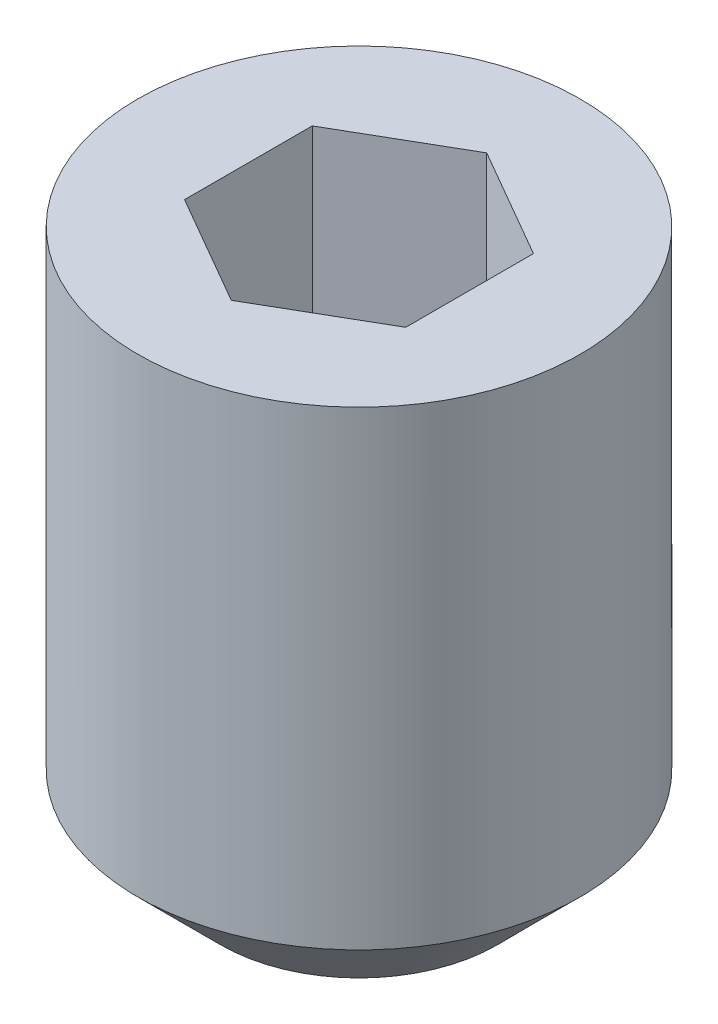
SolidWorks part; units mm, degrees
ref_plane "Front Plane" through (0, 0, 0) normal (0, 0, 1) x (1, 0, 0)
ref_plane "Top Plane" through (0, 0, 0) normal (0, 1, 0) x (1, 0, 0)
ref_plane "Right Plane" through (0, 0, 0) normal (1, 0, 0) x (0, 0, -1)
sketch "Sketch1" plane through (0, 0, 0) normal (0, 0, 1) x (1, 0, 0)
  line L0 (0, 5) -> (0, 0) construction
  line L1 (0, 5) -> (2, 5)
  line L2 (2, 5) -> (2, 0)
  line L3 (2, 0) -> (0, 0)
  line L4 (0, 5) -> (0, 0)
  dimension "SS_M" = 4
  dimension "SLH" = 5
revolve "Revolve1" add sketch "Sketch1" angle 360 about L0
cosmetic thread "Cosmetic Thread1" parameters "SS_D1_s"=3.22
sketch "Sketch2" plane through (0, 0, 0) normal (0, 0, 1) x (1, 0, 0)
  line L0 (0, 5) -> (0, 2.9226) construction
  line L1 (0, 5) -> (1, 5)
  line L2 (1, 5) -> (1, 3.5)
  line L3 (1, 3.5) -> (0, 2.9226)
  line L4 (0, 5) -> (0, 2.9226)
  line L5 (2, 5) -> (-2, 5) construction
  dimension "D3" = 60
  dimension "SS_C" = 1.5
  dimension "SS_B" = 2
revolve "Cut-Revolve1" cut sketch "Sketch2" angle 360 about L0
sketch "Sketch3" plane through (0, 5, 0) normal (0, 1, 0) x (1, 0, 0)
  line L1 (0, 1.1547) -> (-1, 0.5774)
  line L2 (-1, 0.5774) -> (-1, -0.5774)
  line L3 (-1, -0.5774) -> (0, -1.1547)
  line L4 (0, -1.1547) -> (1, -0.5774)
  line L5 (1, -0.5774) -> (1, 0.5774)
  line L6 (1, 0.5774) -> (0, 1.1547)
  circle A0 centre (0, 0) radius 1 construction
  circle A1 centre (0, 0) radius 1 construction
extrude "Cut-Extrude1" cut sketch "Sketch3" against normal blind 1.5
sketch "Sketch4" plane through (0, 0, 0) normal (0, 0, 1) x (1, 0, 0)
  line L0 (1.25, 0) -> (2, 0)
  line L1 (2, 0) -> (2, 0.75)
  line L2 (2, 0.75) -> (1.25, 0)
  line L4 (-2, 0) -> (2, 0) construction
  line L5 (0, 0) -> (0, 5) construction
  line L6 (2, 5) -> (-2, 5) construction
  line L7 (2, 5) -> (2, 0) construction
  dimension "D1" = 45
  dimension "SS_D_s" = 2.5
revolve "Cut-Revolve2" cut sketch "Sketch4" angle 360 about L5
